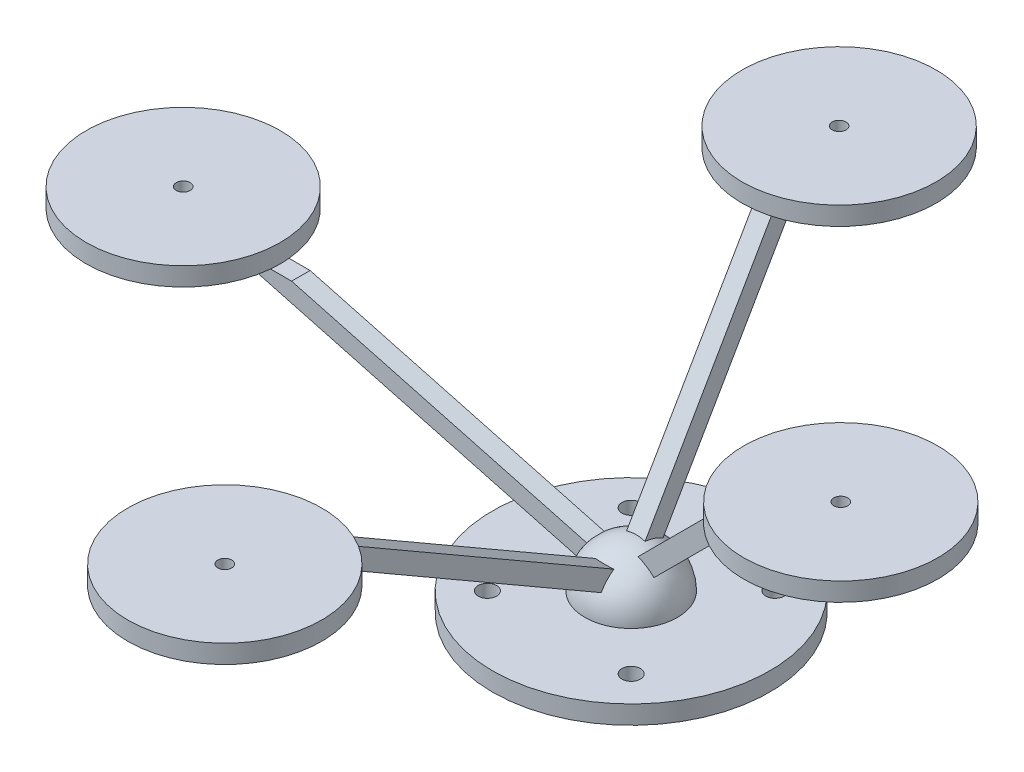
SolidWorks part; units mm, degrees
ref_plane "前视基准面" through (0, 0, 0) normal (0, 0, 1) x (1, 0, 0)
ref_plane "上视基准面" through (0, 0, 0) normal (0, 1, 0) x (1, 0, 0)
ref_plane "右视基准面" through (0, 0, 0) normal (1, 0, 0) x (0, 0, -1)
sketch "草图1" plane through (0, 0, 0) normal (0, 1, 0) x (1, 0, 0)
  line L0 (-23.4221, 0) -> (25.8766, 0) construction
  line L1 (0, 26.1921) -> (0, -25.0701) construction
  line L2 (-18.9498, 18.9498) -> (18.8862, -18.8862) construction
  line L3 (18.9424, 18.9424) -> (-20.2044, -20.2044) construction
  circle A0 centre (0, 0) radius 15
  circle A1 centre (0, 0) radius 11 construction
  circle A2 centre (7.7782, 7.7782) radius 1
  circle A3 centre (-7.7782, 7.7782) radius 1
  circle A4 centre (-7.7782, -7.7782) radius 1
  circle A5 centre (7.7782, -7.7782) radius 1
  dimension "D1" = 30
  dimension "D4" = 22
  dimension "D5" = 2
  dimension "D2" = 45
  dimension "D3" = 45
extrude "凸台-拉伸1" add sketch "草图1" along normal blind 2
sketch "草图2" plane through (0, 0, 0) normal (1, 0, 0) x (0, 0, -1)
  line L0 (0, 2) -> (0, 7)
  line L1 (15, 2) -> (-15, 2) construction
  line L2 (0, 2) -> (5, 2)
  arc A0 (0, 7) -> (5, 2) centre (0, 2) cw
  dimension "D1" = 5
revolve "旋转1" add sketch "草图2" angle 360 about L0
sketch "草图3" plane through (0, 0, 0) normal (0, 0, 1) x (1, 0, 0)
  line L0 (0, 2) -> (0, 9.7216) construction
  line L1 (15, 2) -> (-15, 2) construction
  line L2 (0, 2) -> (17.6777, 19.6777)
  line L3 (8.7782, 2) -> (6.7782, 2) construction
  line L4 (0, 4.8284) -> (14.8492, 19.6777)
  line L6 (14.8492, 19.6777) -> (17.6777, 19.6777)
  line L7 (0, 2) -> (-43.4667, 13.6469)
  line L8 (-35.7393, 13.6469) -> (0, 4.0706)
  line L10 (-43.4667, 13.6469) -> (-35.7393, 13.6469)
  line L11 (0, 4.8284) -> (0, 4.0706)
  dimension "D1" = 45
  dimension "D2" = 25
  dimension "D3" = 2
  dimension "D4" = 15
  dimension "D5" = 45
  dimension "D6" = 2
extrude "凸台-拉伸2" add sketch "草图3" along normal mid plane 2
sketch "草图4" plane through (0, 19.6777, 0) normal (0, 1, 0) x (1, 0, 0)
  line L0 (17.6777, -1) -> (17.6777, 1) construction
  circle A0 centre (22.6777, 0) radius 10.5
  circle A1 centre (22.6777, 0) radius 0.75
  dimension "D1" = 21
  dimension "D2" = 1.5
  dimension "D3" = 5
extrude "凸台-拉伸3" add sketch "草图4" along normal blind 2
sketch "草图5" plane through (0, 13.6469, 0) normal (0, 1, 0) x (1, 0, 0)
  line L0 (-43.4667, -1) -> (-43.4667, 1) construction
  circle A0 centre (-48.4667, 0) radius 10.5
  circle A1 centre (-48.4667, 0) radius 0.75
  dimension "D1" = 21
  dimension "D2" = 1.5
  dimension "D3" = 5
extrude "凸台-拉伸4" add sketch "草图5" along normal blind 2
sketch "草图6" plane through (0, 0, 0) normal (1, 0, 0) x (0, 0, -1)
  line L0 (0, 0) -> (0, 10.6928) construction
  line L1 (0, 2) -> (17.5, 32.3109)
  line L2 (15, 2) -> (-15, 2) construction
  line L3 (8.7782, 2) -> (6.7782, 2) construction
  line L4 (0, 6) -> (15.1906, 32.3109)
  line L5 (15.1906, 32.3109) -> (17.5, 32.3109)
  line L6 (0, 2) -> (-38.9711, 24.5)
  line L7 (0, 4.3094) -> (-34.9711, 24.5)
  line L8 (-38.9711, 24.5) -> (-34.9711, 24.5)
  line L10 (0, 6) -> (0, 4.3094)
  dimension "D1" = 60
  dimension "D2" = 35
  dimension "D3" = 2
  dimension "D4" = 30
  dimension "D5" = 45
  dimension "D6" = 2
extrude "凸台-拉伸5" add sketch "草图6" along normal mid plane 2
sketch "草图7" plane through (0, 32.3109, 0) normal (0, 1, 0) x (1, 0, 0)
  line L0 (1, 17.5) -> (-1, 17.5) construction
  circle A0 centre (0, 22.5) radius 10.5
  circle A1 centre (0, 22.5) radius 0.75
  dimension "D1" = 21
  dimension "D2" = 1.5
  dimension "D3" = 5
extrude "凸台-拉伸6" add sketch "草图7" along normal blind 2
sketch "草图8" plane through (0, 24.5, 0) normal (0, 1, 0) x (1, 0, 0)
  line L0 (1, -38.9711) -> (-1, -38.9711) construction
  circle A0 centre (0, -43.9711) radius 10.5
  circle A1 centre (0, -43.9711) radius 0.75
  dimension "D1" = 1.5
  dimension "D2" = 21
  dimension "D3" = 5
extrude "凸台-拉伸7" add sketch "草图8" along normal blind 2
